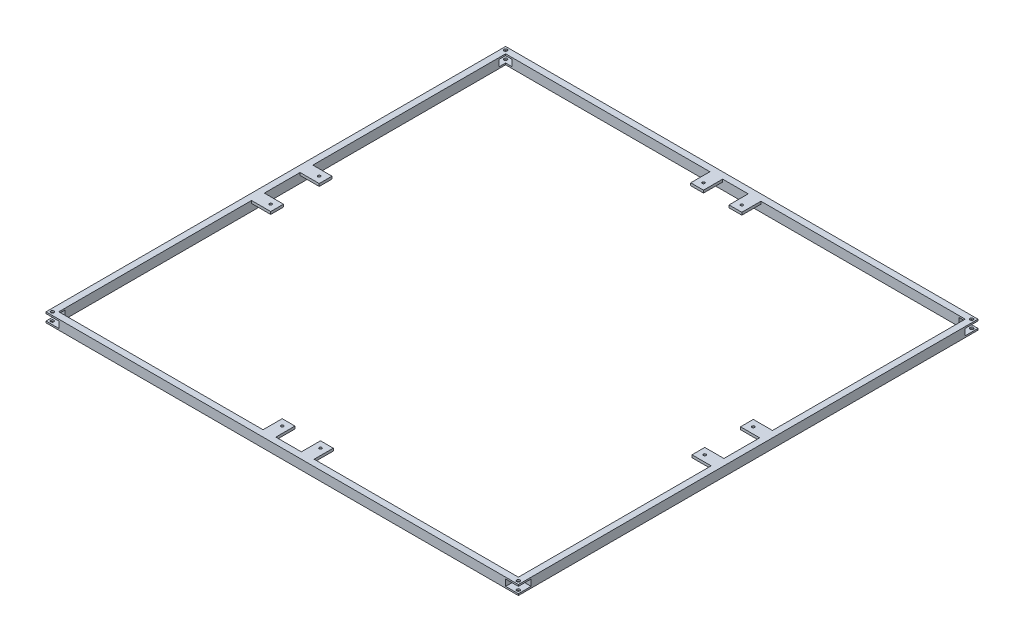
SolidWorks part; units mm, degrees
ref_plane "Front Plane" through (0, 0, 0) normal (0, 0, 1) x (1, 0, 0)
ref_plane "Top Plane" through (0, 0, 0) normal (0, 1, 0) x (1, 0, 0)
ref_plane "Right Plane" through (0, 0, 0) normal (1, 0, 0) x (0, 0, -1)
sketch "Sketch1" plane through (0, 0, 0) normal (0, 1, 0) x (1, 0, 0)
  line L1 (-360, 350) -> (360, 350)
  line L2 (-360, 350) -> (-360, -350)
  line L3 (-360, -350) -> (360, -350)
  line L4 (360, 350) -> (360, -350)
  line L5 (-370, 360) -> (370, 360)
  line L6 (-370, 360) -> (-370, -360)
  line L7 (-370, -360) -> (370, -360)
  line L8 (370, 360) -> (370, -360)
  dimension "D1" = 720
  dimension "D2" = 700
  dimension "D3" = 10
  dimension "D4" = 10
  dimension "D5" = 720
  dimension "D6" = 10
  dimension "D7" = 350
  dimension "D8" = 360
extrude "Boss-Extrude1" add sketch "Sketch1" along normal blind 15
sketch "Sketch2" plane through (0, 15, 0) normal (0, 1, 0) x (1, 0, 0)
  line L0 (370, 360) -> (-370, 360) construction
  line L1 (-370, 360) -> (-370, -360) construction
  line L2 (370, -360) -> (370, 360) construction
  line L3 (-370, -360) -> (370, -360) construction
  circle A0 centre (-365, 355) radius 2.5
  circle A1 centre (365, 355) radius 2.5
  circle A2 centre (365, -355) radius 2.5
  circle A3 centre (-365, -355) radius 2.5
  point P14 (326.2666, 366.4943)
  point P17 (323.3837, 361.6457)
  dimension "D1" = 5
  dimension "D4" = 5
  dimension "D5" = 5
  dimension "D10" = 5
  dimension "D2" = 5
  dimension "D3" = 5
  dimension "D6" = 5
  dimension "D7" = 5
  dimension "D8" = 5
  dimension "D9" = 5
  dimension "D11" = 5
  dimension "D12" = 5
extrude "Cut-Extrude1" cut sketch "Sketch2" against normal through all
sketch "Sketch3" plane through (0, 0, 360) normal (0, 0, 1) x (1, 0, 0)
  line L0 (-370, 15) -> (-370, 0) construction
  line L1 (-370, 12.5) -> (-350, 12.5)
  line L2 (-370, 12.5) -> (-370, 2.5)
  line L3 (-370, 2.5) -> (-350, 2.5)
  line L4 (-350, 12.5) -> (-350, 2.5)
  line L5 (-370, 0) -> (370, 0) construction
  line L6 (370, 15) -> (370, 0) construction
  line L7 (350, 12.5) -> (370, 12.5)
  line L8 (350, 12.5) -> (350, 2.5)
  line L9 (350, 2.5) -> (370, 2.5)
  line L10 (370, 12.5) -> (370, 2.5)
  line L11 (-370, 15) -> (370, 15) construction
  dimension "D1" = 10
  dimension "D2" = 2.5
  dimension "D3" = 20
  dimension "D4" = 20
  dimension "D5" = 10
  dimension "D6" = 2.5
extrude "Cut-Extrude2" cut sketch "Sketch3" against normal blind 20
sketch "Sketch5" plane through (0, 0, -360) normal (0, 0, -1) x (-1, 0, 0)
  line L0 (-370, 15) -> (-370, 0) construction
  line L1 (-370, 12.5) -> (-350, 12.5)
  line L2 (-370, 12.5) -> (-370, 2.5)
  line L3 (-370, 2.5) -> (-350, 2.5)
  line L4 (-350, 12.5) -> (-350, 2.5)
  line L5 (-370, 15) -> (370, 15) construction
  line L6 (370, 15) -> (370, 0) construction
  line L7 (350, 12.5) -> (370, 12.5)
  line L8 (350, 12.5) -> (350, 2.5)
  line L9 (350, 2.5) -> (370, 2.5)
  line L10 (370, 12.5) -> (370, 2.5)
  dimension "D1" = 10
  dimension "D2" = 2.5
  dimension "D3" = 20
  dimension "D4" = 20
  dimension "D5" = 10
  dimension "D6" = 2.5
extrude "Cut-Extrude3" cut sketch "Sketch5" against normal blind 20
sketch "Sketch6" plane through (0, 15, 0) normal (0, 1, 0) x (1, 0, 0)
  line L0 (360, 350) -> (-360, 350) construction
  line L1 (-360, 350) -> (-360, -350) construction
  line L2 (-40, 350) -> (-20, 350)
  line L3 (-40, 350) -> (-40, 320)
  line L4 (-40, 320) -> (-20, 320)
  line L5 (-20, 350) -> (-20, 320)
  line L6 (20, 350) -> (40, 350)
  line L7 (20, 350) -> (20, 320)
  line L8 (20, 320) -> (40, 320)
  line L9 (40, 350) -> (40, 320)
  line L10 (360, -350) -> (360, 350) construction
  line L11 (-211.469, 0) -> (209.4299, 0) construction
  line L12 (40, -350) -> (40, -320)
  line L13 (20, -320) -> (40, -320)
  line L14 (20, -350) -> (20, -320)
  line L15 (20, -350) -> (40, -350)
  line L16 (-20, -350) -> (-20, -320)
  line L17 (-40, -320) -> (-20, -320)
  line L18 (-40, -350) -> (-40, -320)
  line L19 (-40, -350) -> (-20, -350)
  line L20 (0, 152.342) -> (0, -166.5735) construction
  line L21 (-330, -28) -> (-330, -48)
  line L22 (-360, 28) -> (-330, 28)
  line L23 (-360, 28) -> (-360, 48)
  line L24 (-360, 48) -> (-330, 48)
  line L25 (-330, 28) -> (-330, 48)
  line L30 (-360, -48) -> (-330, -48)
  line L31 (-360, -28) -> (-360, -48)
  line L32 (-360, -28) -> (-330, -28)
  line L33 (360, -28) -> (330, -28)
  line L34 (360, -28) -> (360, -48)
  line L35 (360, -48) -> (330, -48)
  line L36 (330, 28) -> (330, 48)
  line L37 (360, 48) -> (330, 48)
  line L38 (360, 28) -> (360, 48)
  line L39 (360, 28) -> (330, 28)
  line L40 (330, -28) -> (330, -48)
  dimension "D1" = 320
  dimension "D2" = 20
  dimension "D3" = 30
  dimension "D4" = 20
  dimension "D5" = 320
  dimension "D6" = 30
  dimension "D7" = 302
  dimension "D8" = 20
  dimension "D9" = 30
extrude "Boss-Extrude2" add sketch "Sketch6" against normal blind 4
sketch "Sketch7" plane through (0, 15, 0) normal (0, 1, 0) x (1, 0, 0)
  line L1 (-40, 350) -> (-360, 350) construction
  line L2 (-20, 320) -> (-20, 350) construction
  line L3 (-122.2142, 0) -> (113.7072, 0) construction
  line L4 (0, 75.0505) -> (0, -78.0241) construction
  line L5 (360, 48) -> (360, 350) construction
  line L6 (360, 48) -> (330, 48) construction
  circle A0 centre (-30, 330) radius 2
  circle A1 centre (30, 330) radius 2
  circle A2 centre (30, -330) radius 2
  circle A3 centre (-30, -330) radius 2
  circle A4 centre (340, 38) radius 2
  circle A6 centre (340, -38) radius 2
  circle A7 centre (-340, -38) radius 2
  circle A8 centre (-340, 38) radius 2
  point P21 (0, 0)
  dimension "D1" = 4
  dimension "D4" = 4
  dimension "D5" = 20
  dimension "D2" = 20
  dimension "D3" = 10
  dimension "D6" = 10
extrude "Cut-Extrude4" cut sketch "Sketch7" against normal blind 4
